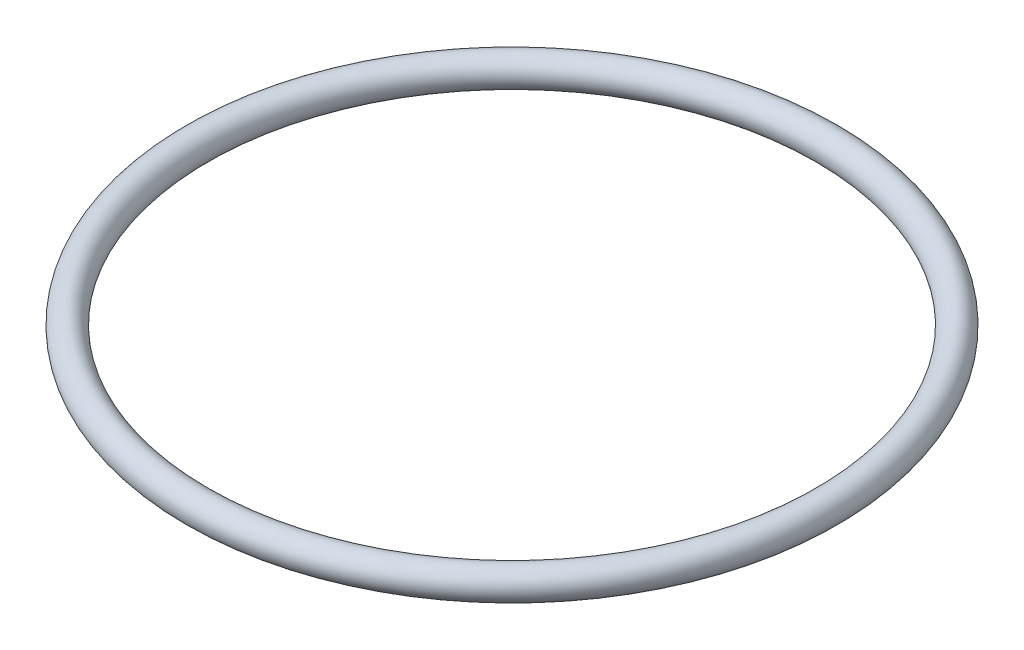
SolidWorks part; units mm, degrees
material "Rubber"
ref_plane "Front Plane" through (0, 0, 0) normal (0, 0, 1) x (1, 0, 0)
ref_plane "Top Plane" through (0, 0, 0) normal (0, 1, 0) x (1, 0, 0)
ref_plane "Right Plane" through (0, 0, 0) normal (1, 0, 0) x (0, 0, -1)
sketch "Sketch1" plane through (0, 0, 0) normal (0, 0, 1) x (1, 0, 0)
  line L0 (0, -3.4925) -> (0, 3.4925) construction
  circle A1 centre (-73.025, 0) radius 3.4925
  point P3 (-69.5325, 0)
  point P4 (-76.5175, 0)
  point P6 (0, 0)
  dimension "D2" = 139.065
  dimension "D1" = 6.985
  dimension "D3" = 153.035
revolve "O-Ring Revolve" add sketch "Sketch1" angle 360 about L0
sketch "O-Ring Profile" plane through (0, 0, 0) normal (0, 1, 0) x (1, 0, 0)
  circle A0 centre (0, 0) radius 50.8 construction
  dimension "D1" = 101.6
